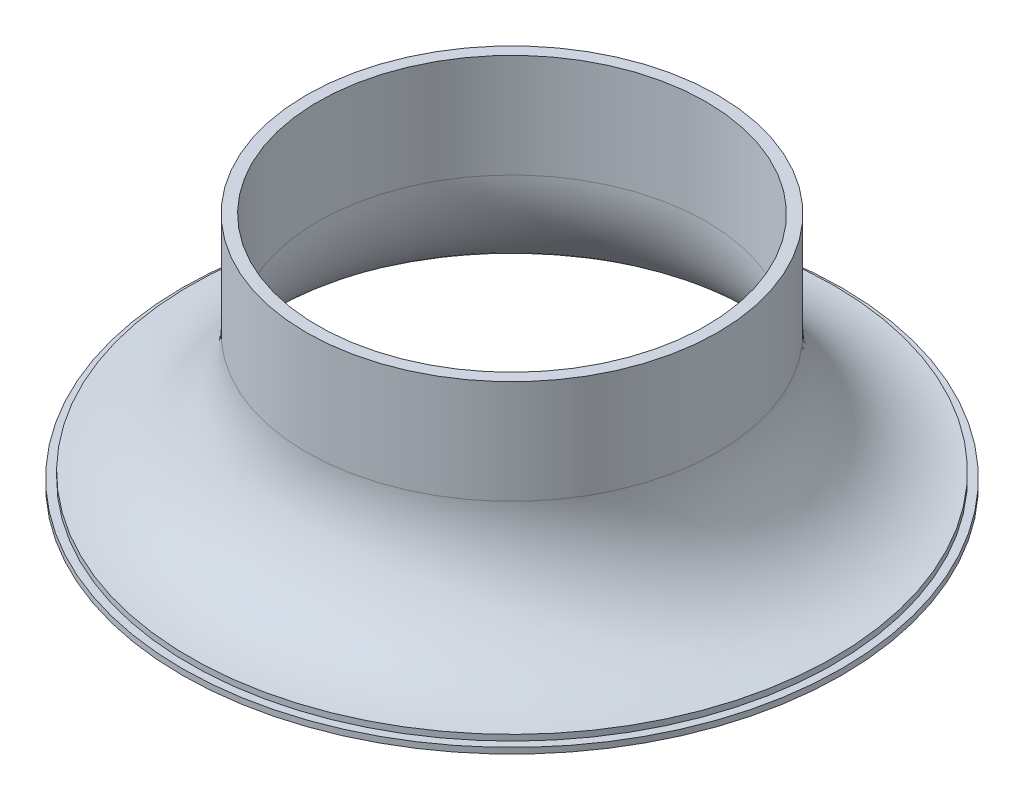
SolidWorks part; units mm, degrees
ref_plane "Ön Düzlem" through (0, 0, 0) normal (0, 0, 1) x (1, 0, 0)
ref_plane "Üst Düzlem" through (0, 0, 0) normal (0, 1, 0) x (1, 0, 0)
ref_plane "Sağ Düzlem" through (0, 0, 0) normal (1, 0, 0) x (0, 0, -1)
sketch "Çizim1" plane through (0, 0, 0) normal (0, 0, 1) x (1, 0, 0)
  line L0 (0, 0) -> (0, 7.2623) construction
  line L1 (-25.1, 9.2704) -> (-25.1, -4.1296)
  line L2 (-25.1, -4.1296) -> (-42.06, -4.1296) construction
  line L3 (-42.06, -4.1296) -> (-42.06, -19.5896) construction
  line L4 (-26.6, 9.2704) -> (-26.6, -4.1296)
  line L5 (-26.6, 9.2704) -> (-25.1, 9.2704)
  line L6 (-42.06, -21.0896) -> (-42.65, -21.0896)
  line L7 (-42.65, -21.0896) -> (-42.65, -20.3396)
  line L8 (-42.65, -20.3396) -> (-42.06, -20.3396)
  line L10 (-42.06, -20.3396) -> (-41.65, -20.3396)
  line L12 (-41.65, -20.3396) -> (-41.65, -19.5841)
  line L13 (-42.06, -20.3396) -> (-42.06, -21.0896) construction
  arc A0 (-42.06, -21.0896) -> (-25.1, -4.1296) centre (-42.06, -4.1296) ccw
  arc A1 (-41.65, -19.5841) -> (-26.6, -4.1296) centre (-42.06, -4.1296) ccw
  arc A2 (-42.06, -19.5896) -> (-26.6, -4.1296) centre (-42.06, -4.1296) ccw construction
  dimension "D3" = 33.92
  dimension "D1" = 13.4
  dimension "D2" = 25.1
  dimension "D4" = 1.5
  dimension "D5" = 0.59
  dimension "D6" = 0.75
  dimension "D7" = 0.41
revolve "Döndür1" add sketch "Çizim1" angle 360 about L0
